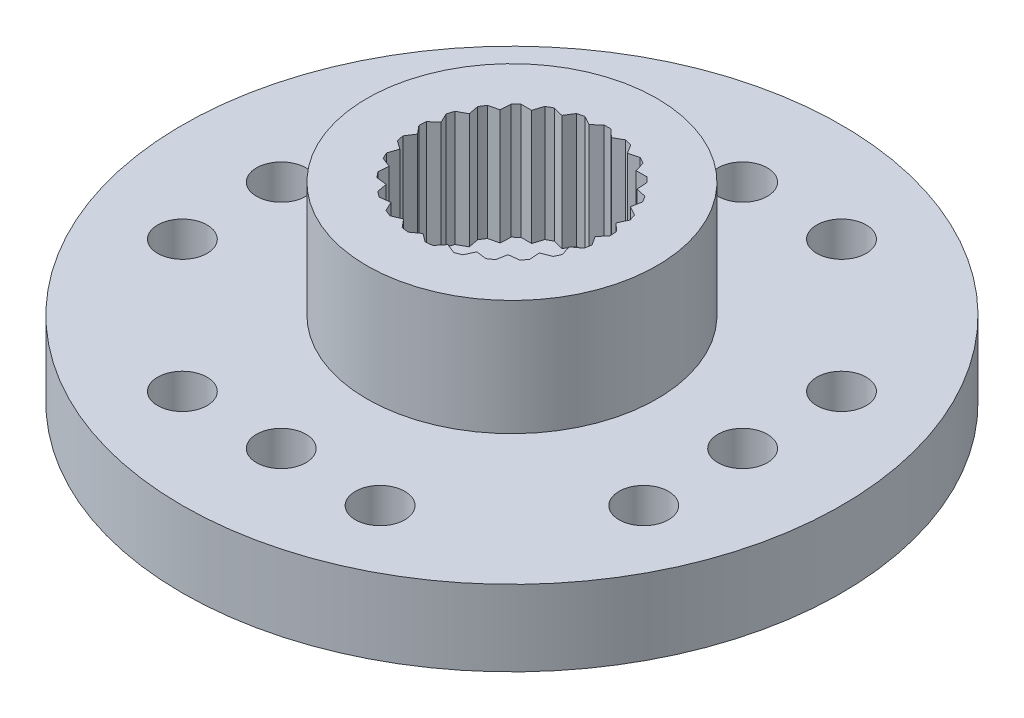
SolidWorks part; units mm, degrees
material "ABS"
ref_plane "Front Plane" through (0, 0, 0) normal (0, 0, 1) x (1, 0, 0)
ref_plane "Top Plane" through (0, 0, 0) normal (0, 1, 0) x (1, 0, 0)
ref_plane "Right Plane" through (0, 0, 0) normal (1, 0, 0) x (0, 0, -1)
sketch "Sketch2" plane through (0, 0, 0) normal (0, 1, 0) x (1, 0, 0)
  circle A0 centre (0, 0) radius 6
  circle A1 centre (0, 0) radius 1.5
  dimension "D1" = 12
  dimension "D2" = 3
extrude "Boss-Extrude1" add sketch "Sketch2" along normal mid plane 2.3
sketch "Sketch3" plane through (0, 1.15, 0) normal (0, 1, 0) x (1, 0, 0)
  line L0 (0, 0) -> (0, 2.9) construction
  line L3 (0, 0) -> (0.376, 2.9763) construction
  line L52 (0.1074, 2.898) -> (0.3384, 2.6787)
  line L53 (-0.1074, 2.898) -> (-0.3384, 2.6787)
  line L54 (0.8248, 2.7802) -> (0.9939, 2.5104)
  line L55 (0.6167, 2.8337) -> (0.3384, 2.6787)
  line L56 (1.4903, 2.4878) -> (1.587, 2.1843)
  line L57 (1.302, 2.5913) -> (0.9939, 2.5104)
  line L58 (2.0621, 2.039) -> (2.0804, 1.721)
  line L59 (1.9055, 2.1861) -> (1.587, 2.1843)
  line L60 (2.5044, 1.4621) -> (2.443, 1.1496)
  line L61 (2.3893, 1.6435) -> (2.0804, 1.721)
  line L62 (2.7894, 0.7934) -> (2.6522, 0.5059)
  line L63 (2.723, 0.9977) -> (2.443, 1.1496)
  line L64 (2.899, 0.0748) -> (2.6947, -0.1695)
  line L65 (2.8855, 0.2892) -> (2.6522, 0.5059)
  line L66 (2.8265, -0.6486) -> (2.5679, -0.8343)
  line L67 (2.8668, -0.4375) -> (2.6947, -0.1695)
  line L68 (2.5765, -1.3311) -> (2.2797, -1.4467)
  line L69 (2.6679, -1.1367) -> (2.5679, -0.8343)
  line L70 (2.1645, -1.93) -> (1.8483, -1.9682)
  line L71 (2.3014, -1.7645) -> (2.2797, -1.4467)
  line L72 (1.6165, -2.4077) -> (1.3007, -2.366)
  line L73 (1.7903, -2.2814) -> (1.8483, -1.9682)
  line L74 (0.967, -2.734) -> (0.6715, -2.6152)
  line L75 (1.1667, -2.655) -> (1.3007, -2.366)
  line L76 (0.2566, -2.8886) -> (0, -2.7)
  line L77 (0.4698, -2.8617) -> (0.6715, -2.6152)
  line L78 (-0.4698, -2.8617) -> (-0.6715, -2.6152)
  line L79 (-0.2566, -2.8886) -> (0, -2.7)
  line L80 (-1.1667, -2.655) -> (-1.3007, -2.366)
  line L81 (-0.967, -2.734) -> (-0.6715, -2.6152)
  line L82 (-1.7903, -2.2814) -> (-1.8483, -1.9682)
  line L83 (-1.6165, -2.4077) -> (-1.3007, -2.366)
  line L84 (-2.3014, -1.7645) -> (-2.2797, -1.4467)
  line L85 (-2.1645, -1.93) -> (-1.8483, -1.9682)
  line L86 (-2.6679, -1.1367) -> (-2.5679, -0.8343)
  line L87 (-2.5765, -1.3311) -> (-2.2797, -1.4467)
  line L88 (-2.8668, -0.4375) -> (-2.6947, -0.1695)
  line L89 (-2.8265, -0.6486) -> (-2.5679, -0.8343)
  line L90 (-2.8855, 0.2892) -> (-2.6522, 0.5059)
  line L91 (-2.899, 0.0748) -> (-2.6947, -0.1695)
  line L92 (-2.723, 0.9977) -> (-2.443, 1.1496)
  line L93 (-2.7894, 0.7934) -> (-2.6522, 0.5059)
  line L94 (-2.3893, 1.6435) -> (-2.0804, 1.721)
  line L95 (-2.5044, 1.4621) -> (-2.443, 1.1496)
  line L96 (-1.9055, 2.1861) -> (-1.587, 2.1843)
  line L97 (-2.0621, 2.039) -> (-2.0804, 1.721)
  line L98 (-1.302, 2.5913) -> (-0.9939, 2.5104)
  line L99 (-1.4903, 2.4878) -> (-1.587, 2.1843)
  line L100 (-0.6167, 2.8337) -> (-0.3384, 2.6787)
  line L101 (-0.8248, 2.7802) -> (-0.9939, 2.5104)
  line L102 (-2.533, 1.6075) -> (-2.3893, 1.6435) construction
  line L103 (-2.533, 1.6075) -> (-2.5044, 1.4621) construction
  line L104 (-2.8532, 0.9271) -> (-2.723, 0.9977) construction
  line L105 (-2.8532, 0.9271) -> (-2.7894, 0.7934) construction
  line L106 (-2.9941, 0.1884) -> (-2.8855, 0.2892) construction
  line L107 (-2.9941, 0.1884) -> (-2.899, 0.0748) construction
  line L108 (-2.9469, -0.5621) -> (-2.8668, -0.4375) construction
  line L109 (-2.9469, -0.5621) -> (-2.8265, -0.6486) construction
  line L110 (0, 3) -> (0.1074, 2.898) construction
  line L111 (0, 2.9) -> (0, 3) construction
  line L112 (0, 3) -> (-0.1074, 2.898) construction
  line L113 (-0.7461, 2.9057) -> (-0.6167, 2.8337) construction
  line L114 (-0.7461, 2.9057) -> (-0.8248, 2.7802) construction
  line L115 (-1.4453, 2.6289) -> (-1.302, 2.5913) construction
  line L116 (-1.4453, 2.6289) -> (-1.4903, 2.4878) construction
  line L117 (-2.0536, 2.1869) -> (-1.9055, 2.1861) construction
  line L118 (-2.0536, 2.1869) -> (-2.0621, 2.039) construction
  line L119 (-2.7145, -1.2773) -> (-2.6679, -1.1367) construction
  line L120 (-2.7145, -1.2773) -> (-2.5765, -1.3311) construction
  line L121 (-2.3115, -1.9123) -> (-2.3014, -1.7645) construction
  line L122 (-2.3115, -1.9123) -> (-2.1645, -1.93) construction
  line L123 (-1.7634, -2.4271) -> (-1.7903, -2.2814) construction
  line L124 (-1.7634, -2.4271) -> (-1.6165, -2.4077) construction
  line L125 (-1.1044, -2.7893) -> (-1.1667, -2.655) construction
  line L126 (-1.1044, -2.7893) -> (-0.967, -2.734) construction
  line L127 (-0.376, -2.9763) -> (-0.4698, -2.8617) construction
  line L128 (-0.376, -2.9763) -> (-0.2566, -2.8886) construction
  line L129 (0.376, -2.9763) -> (0.2566, -2.8886) construction
  line L130 (0.376, -2.9763) -> (0.4698, -2.8617) construction
  line L131 (1.1044, -2.7893) -> (0.967, -2.734) construction
  line L132 (1.1044, -2.7893) -> (1.1667, -2.655) construction
  line L133 (1.7634, -2.4271) -> (1.6165, -2.4077) construction
  line L134 (1.7634, -2.4271) -> (1.7903, -2.2814) construction
  line L135 (2.3115, -1.9123) -> (2.3014, -1.7645) construction
  line L136 (2.3115, -1.9123) -> (2.1645, -1.93) construction
  line L137 (2.7145, -1.2773) -> (2.6679, -1.1367) construction
  line L138 (2.7145, -1.2773) -> (2.5765, -1.3311) construction
  line L139 (2.9469, -0.5621) -> (2.8668, -0.4375) construction
  line L140 (2.9469, -0.5621) -> (2.8265, -0.6486) construction
  line L141 (2.9941, 0.1884) -> (2.8855, 0.2892) construction
  line L142 (2.9941, 0.1884) -> (2.899, 0.0748) construction
  line L143 (2.8532, 0.9271) -> (2.723, 0.9977) construction
  line L144 (2.8532, 0.9271) -> (2.7894, 0.7934) construction
  line L145 (2.533, 1.6075) -> (2.3893, 1.6435) construction
  line L146 (2.533, 1.6075) -> (2.5044, 1.4621) construction
  line L147 (2.0536, 2.1869) -> (1.9055, 2.1861) construction
  line L148 (2.0536, 2.1869) -> (2.0621, 2.039) construction
  line L149 (1.4453, 2.6289) -> (1.302, 2.5913) construction
  line L150 (1.4453, 2.6289) -> (1.4903, 2.4878) construction
  line L151 (0.7461, 2.9057) -> (0.6167, 2.8337) construction
  line L152 (0.7461, 2.9057) -> (0.8248, 2.7802) construction
  circle A0 centre (0, 0) radius 4.4
  circle A1 centre (0, 0) radius 3 construction
  circle A2 centre (0, 0) radius 2.7 construction
  arc A3 (-0.6167, 2.8337) -> (-0.8248, 2.7802) centre (0, 0) ccw
  arc A4 (-0.1074, 2.898) -> (-0.6167, 2.8337) centre (0, 0) ccw construction
  arc A5 (-0.8248, 2.7802) -> (-1.302, 2.5913) centre (0, 0) ccw construction
  arc A6 (-1.302, 2.5913) -> (-1.4903, 2.4878) centre (0, 0) ccw
  arc A7 (-1.4903, 2.4878) -> (-1.9055, 2.1861) centre (0, 0) ccw construction
  arc A8 (-1.9055, 2.1861) -> (-2.0621, 2.039) centre (0, 0) ccw
  arc A9 (-2.0621, 2.039) -> (-2.3893, 1.6435) centre (0, 0) ccw construction
  arc A10 (-2.3893, 1.6435) -> (-2.5044, 1.4621) centre (0, 0) ccw
  arc A11 (-2.5044, 1.4621) -> (-2.723, 0.9977) centre (0, 0) ccw construction
  arc A12 (-2.723, 0.9977) -> (-2.7894, 0.7934) centre (0, 0) ccw
  arc A13 (-2.7894, 0.7934) -> (-2.8855, 0.2892) centre (0, 0) ccw construction
  arc A14 (-2.8855, 0.2892) -> (-2.899, 0.0748) centre (0, 0) ccw
  arc A15 (-2.899, 0.0748) -> (-2.8668, -0.4375) centre (0, 0) ccw construction
  arc A16 (-2.8668, -0.4375) -> (-2.8265, -0.6486) centre (0, 0) ccw
  arc A17 (-2.8265, -0.6486) -> (-2.6679, -1.1367) centre (0, 0) ccw construction
  arc A18 (-2.6679, -1.1367) -> (-2.5765, -1.3311) centre (0, 0) ccw
  arc A19 (-2.5765, -1.3311) -> (-2.3014, -1.7645) centre (0, 0) ccw construction
  arc A20 (-2.3014, -1.7645) -> (-2.1645, -1.93) centre (0, 0) ccw
  arc A21 (-2.1645, -1.93) -> (-1.7903, -2.2814) centre (0, 0) ccw construction
  arc A22 (-1.7903, -2.2814) -> (-1.6165, -2.4077) centre (0, 0) ccw
  arc A23 (-1.6165, -2.4077) -> (-1.1667, -2.655) centre (0, 0) ccw construction
  arc A24 (-1.1667, -2.655) -> (-0.967, -2.734) centre (0, 0) ccw
  arc A25 (-0.967, -2.734) -> (-0.4698, -2.8617) centre (0, 0) ccw construction
  arc A26 (-0.4698, -2.8617) -> (-0.2566, -2.8886) centre (0, 0) ccw
  arc A27 (-0.2566, -2.8886) -> (0.2566, -2.8886) centre (0, 0) ccw construction
  arc A28 (0.2566, -2.8886) -> (0.4698, -2.8617) centre (0, 0) ccw
  arc A29 (0.4698, -2.8617) -> (0.967, -2.734) centre (0, 0) ccw construction
  arc A30 (0.967, -2.734) -> (1.1667, -2.655) centre (0, 0) ccw
  arc A31 (1.1667, -2.655) -> (1.6165, -2.4077) centre (0, 0) ccw construction
  arc A32 (1.6165, -2.4077) -> (1.7903, -2.2814) centre (0, 0) ccw
  arc A33 (1.7903, -2.2814) -> (2.1645, -1.93) centre (0, 0) ccw construction
  arc A34 (2.1645, -1.93) -> (2.3014, -1.7645) centre (0, 0) ccw
  arc A35 (2.3014, -1.7645) -> (2.5765, -1.3311) centre (0, 0) ccw construction
  arc A36 (2.5765, -1.3311) -> (2.6679, -1.1367) centre (0, 0) ccw
  arc A37 (2.6679, -1.1367) -> (2.8265, -0.6486) centre (0, 0) ccw construction
  arc A38 (2.8265, -0.6486) -> (2.8668, -0.4375) centre (0, 0) ccw
  arc A39 (2.8668, -0.4375) -> (2.899, 0.0748) centre (0, 0) ccw construction
  arc A40 (2.899, 0.0748) -> (2.8855, 0.2892) centre (0, 0) ccw
  arc A41 (2.8855, 0.2892) -> (2.7894, 0.7934) centre (0, 0) ccw construction
  arc A42 (2.7894, 0.7934) -> (2.723, 0.9977) centre (0, 0) ccw
  arc A43 (2.723, 0.9977) -> (2.5044, 1.4621) centre (0, 0) ccw construction
  arc A44 (2.5044, 1.4621) -> (2.3893, 1.6435) centre (0, 0) ccw
  arc A45 (2.3893, 1.6435) -> (2.0621, 2.039) centre (0, 0) ccw construction
  arc A46 (2.0621, 2.039) -> (1.9055, 2.1861) centre (0, 0) ccw
  arc A47 (1.9055, 2.1861) -> (1.4903, 2.4878) centre (0, 0) ccw construction
  arc A48 (1.4903, 2.4878) -> (1.302, 2.5913) centre (0, 0) ccw
  arc A49 (1.302, 2.5913) -> (0.8248, 2.7802) centre (0, 0) ccw construction
  arc A50 (0.8248, 2.7802) -> (0.6167, 2.8337) centre (0, 0) ccw
  arc A51 (0.3635, 2.8771) -> (0.1074, 2.898) centre (0, 0) ccw construction
  arc A52 (0.1074, 2.898) -> (-0.1074, 2.898) centre (0, 0) ccw
  arc A53 (0.6167, 2.8337) -> (0.3635, 2.8771) centre (0, 0) ccw construction
  point P84 (0, 0)
  dimension "D1" = 8.8
  dimension "D2" = 5.4
  dimension "D3" = 6
  dimension "D6" = 5.8
  dimension "D4" = 7.2
  dimension "D5" = 25
extrude "Boss-Extrude2" add sketch "Sketch3" along normal blind 3.5
sketch "Sketch4" plane through (0, 0, 0) normal (0, 1, 0) x (1, 0, 0)
  line L0 (0, 0) -> (13, 0) construction
  line L1 (3.9686, 4.5) -> (14.0007, 2.4494)
  line L2 (3.9686, -4.5) -> (14.0007, -2.4494)
  line L3 (13, 0) -> (10, 0) construction
  circle A0 centre (0, 0) radius 6 construction
  arc A1 (3.9686, -4.5) -> (3.9686, 4.5) centre (0, 0) ccw
  arc A2 (14.0007, 2.4494) -> (14.0007, -2.4494) centre (13.5, 0) cw
  circle A3 centre (13, 0) radius 0.75
  circle A4 centre (10, 0) radius 0.75
  circle A5 centre (7, 0) radius 0.75
  dimension "D3" = 2.5
  dimension "D5" = 1.5
  dimension "D2" = 9
  dimension "D7" = 3
  dimension "D4" = 0.5
  dimension "D1" = 13
  dimension "D6" = 3
extrude "Boss-Extrude3" [suppressed] add sketch "Sketch4" along normal mid plane 2.3
pattern_circular "CirPattern1" [suppressed] count 6 over 360
sketch "Sketch5" plane through (0, 0, 0) normal (0, 1, 0) x (1, 0, 0)
  line L0 (3, 7) -> (-3, 7) construction
  circle A0 centre (0, 0) radius 10
  circle A1 centre (0, 7) radius 0.75
  circle A2 centre (-3, 7) radius 0.75
  circle A3 centre (3, 7) radius 0.75
  circle A4 centre (7, 3) radius 0.75
  circle A5 centre (7, 0) radius 0.75
  circle A6 centre (7, -3) radius 0.75
  circle A7 centre (3, -7) radius 0.75
  circle A8 centre (0, -7) radius 0.75
  circle A9 centre (-3, -7) radius 0.75
  circle A10 centre (-7, -3) radius 0.75
  circle A11 centre (-7, 0) radius 0.75
  circle A12 centre (-7, 3) radius 0.75
  circle A13 centre (0, 0) radius 1.5 construction
  circle A14 centre (0, 0) radius 1.5
  point P8 (0, 7)
  point P31 (0, 0)
  dimension "D1" = 1.5
  dimension "D3" = 2.25
  dimension "D4" = 6
  dimension "D2" = 7
  dimension "D5" = 4
extrude "Boss-Extrude4" add sketch "Sketch5" along normal mid plane 2.3
equation "\"N_hole\"= 3"
equation "\"N_horn\"= 6"
equation "\"D6@Sketch4\"=\"N_hole\""
equation "\"D1@CirPattern1\"=\"N_horn\""
equation "\"D1@Sketch4\"=(\"N_hole\" - 1) *3 +7"
